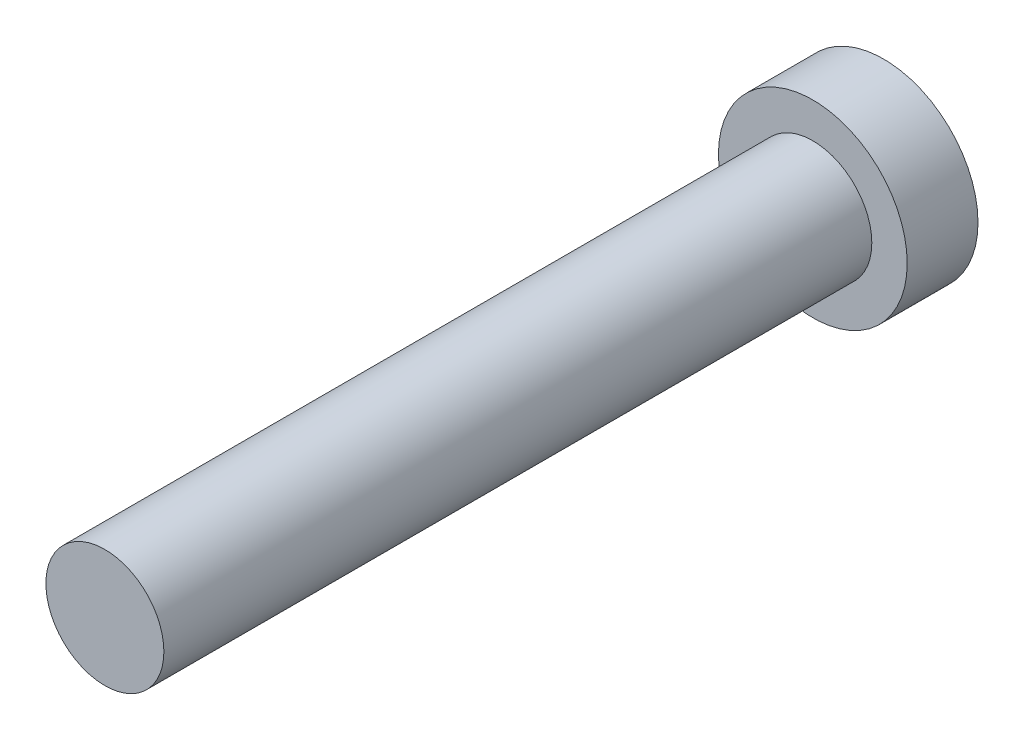
SolidWorks part; units mm, degrees
material "普通碳钢"
ref_plane "前视基准面" through (0, 0, 0) normal (0, 0, 1) x (1, 0, 0)
ref_plane "上视基准面" through (0, 0, 0) normal (0, 1, 0) x (1, 0, 0)
ref_plane "右视基准面" through (0, 0, 0) normal (1, 0, 0) x (0, 0, -1)
sketch "草图1" plane through (0, 0, 0) normal (0, 0, 1) x (1, 0, 0)
  circle A0 centre (0, 0) radius 4
  dimension "D1" = 8
extrude "凸台-拉伸1" add sketch "草图1" along normal blind 3
sketch "草图2" plane through (0, 0, 3) normal (0, 0, 1) x (1, 0, 0)
  circle A0 centre (0, 0) radius 2.5
  dimension "D1" = 5
extrude "凸台-拉伸2" add sketch "草图2" along normal blind 30
